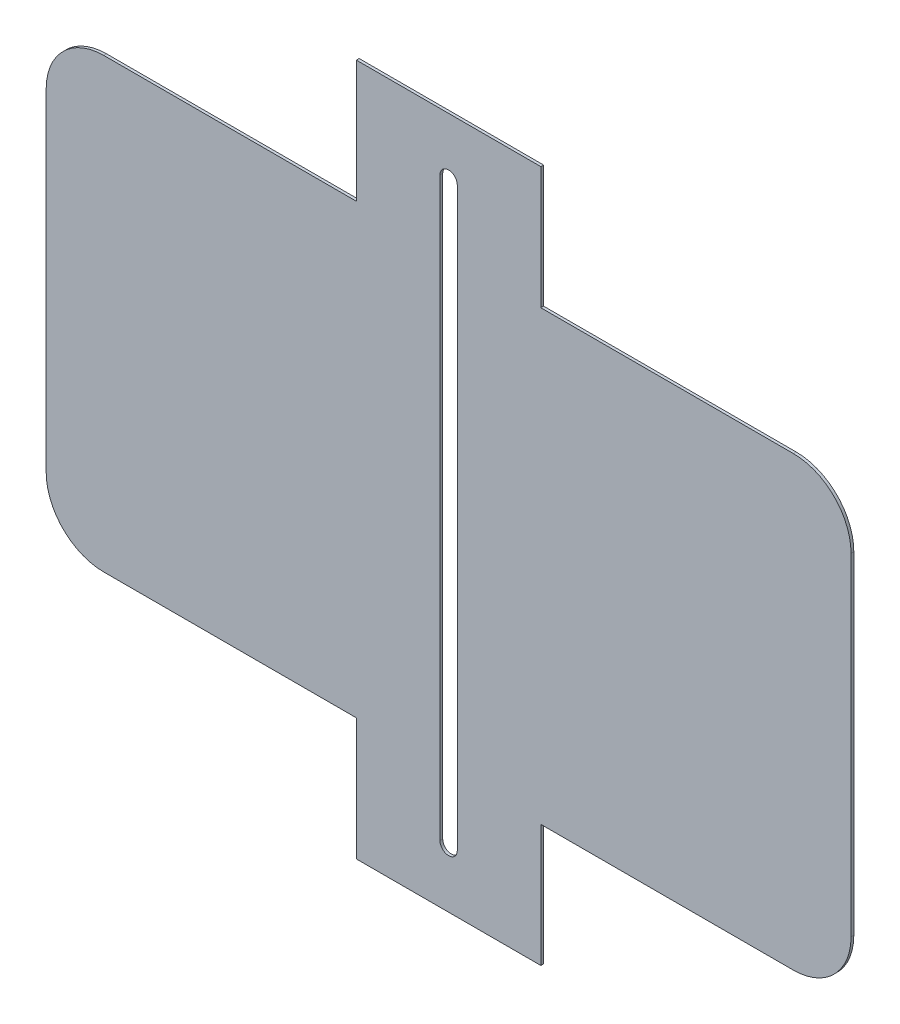
SolidWorks part; units mm, degrees
ref_plane "前基準面" through (0, 0, 0) normal (0, 0, 1) x (1, 0, 0)
ref_plane "上基準面" through (0, 0, 0) normal (0, 1, 0) x (1, 0, 0)
ref_plane "右基準面" through (0, 0, 0) normal (1, 0, 0) x (0, 0, -1)
sketch "草圖1" plane through (0, 0, 0) normal (0, 0, 1) x (1, 0, 0)
  line L0 (0, 30) -> (0, -30) construction
  line L1 (-38, 30) -> (38, 30)
  line L2 (-38, 30) -> (-38, -30)
  line L3 (-38, -30) -> (38, -30)
  line L4 (38, 30) -> (38, -30)
  line L5 (-38, 30) -> (38, -30) construction
  line L6 (-38, -30) -> (38, 30) construction
  line L7 (-38, 30) -> (-8, 30)
  line L8 (-38, 30) -> (-38, 20)
  line L9 (-38, 20) -> (-8, 20)
  line L10 (-8, 30) -> (-8, 20)
  line L11 (-38, 0) -> (38, 0) construction
  line L12 (38, 20) -> (8, 20)
  line L13 (8, 30) -> (8, 20)
  line L14 (38, 30) -> (8, 30)
  line L15 (38, 30) -> (38, 20)
  line L16 (38, -30) -> (8, -30)
  line L17 (8, -30) -> (8, -20)
  line L18 (38, -20) -> (8, -20)
  line L19 (38, -30) -> (38, -20)
  line L20 (-38, -20) -> (-8, -20)
  line L21 (-8, -30) -> (-8, -20)
  line L22 (-38, -30) -> (-8, -30)
  line L23 (-38, -30) -> (-38, -20)
  line L24 (-0.75, 25) -> (-0.75, -25)
  line L25 (0.75, -25) -> (0.75, 25)
  arc A0 (0.75, 25) -> (-0.75, 25) centre (0, 25) ccw
  arc A1 (0.75, -25) -> (-0.75, -25) centre (0, -25) cw
  point P0 (0, 0)
  dimension "D3" = 1.5
  dimension "D1" = 76
  dimension "D2" = 60
  dimension "D4" = 5
  dimension "D5" = 10
  dimension "D6" = 30
extrude "填料-伸長1" add sketch "草圖1" along normal blind 0.24 contours L21 L3 L17 L18 L4 L12 L13 L1 L10 L9 L2 L20 A0
sketch "草圖2" plane through (0, 0, 0.24) normal (0, 0, 1) x (1, 0, 0)
  line L0 (-8, 20) -> (-38, 20)
  line L1 (-38, 20) -> (-38, -20)
  line L2 (-38, -20) -> (-8, -20)
  line L3 (-8, -20) -> (-8, -19.4)
  line L4 (-8, -19.4) -> (-29.9, -19.4)
  line L5 (-34.9, -14.4) -> (-34.9, 14.4)
  line L6 (-29.9, 19.4) -> (-8, 19.4)
  line L7 (-8, 19.4) -> (-8, 20)
  line L8 (0, 30) -> (0, -30) construction
  line L9 (-8, 30) -> (8, 30) construction
  line L10 (-8, -30) -> (8, -30) construction
  line L11 (8, 19.4) -> (8, 20)
  line L12 (29.9, 19.4) -> (8, 19.4)
  line L13 (34.9, -14.4) -> (34.9, 14.4)
  line L14 (8, -19.4) -> (29.9, -19.4)
  line L15 (8, -20) -> (8, -19.4)
  line L16 (38, -20) -> (8, -20)
  line L17 (38, 20) -> (38, -20)
  line L18 (8, 20) -> (38, 20)
  arc A0 (-29.9, -19.4) -> (-34.9, -14.4) centre (-29.9, -14.4) cw
  arc A1 (-34.9, 14.4) -> (-29.9, 19.4) centre (-29.9, 14.4) cw
  arc A2 (34.9, 14.4) -> (29.9, 19.4) centre (29.9, 14.4) ccw
  arc A3 (29.9, -19.4) -> (34.9, -14.4) centre (29.9, -14.4) ccw
  dimension "D4" = 5
  dimension "D1" = 0.6
  dimension "D2" = 0.6
  dimension "D3" = 3.1
extrude "除料-伸長1" cut sketch "草圖2" against normal through all
